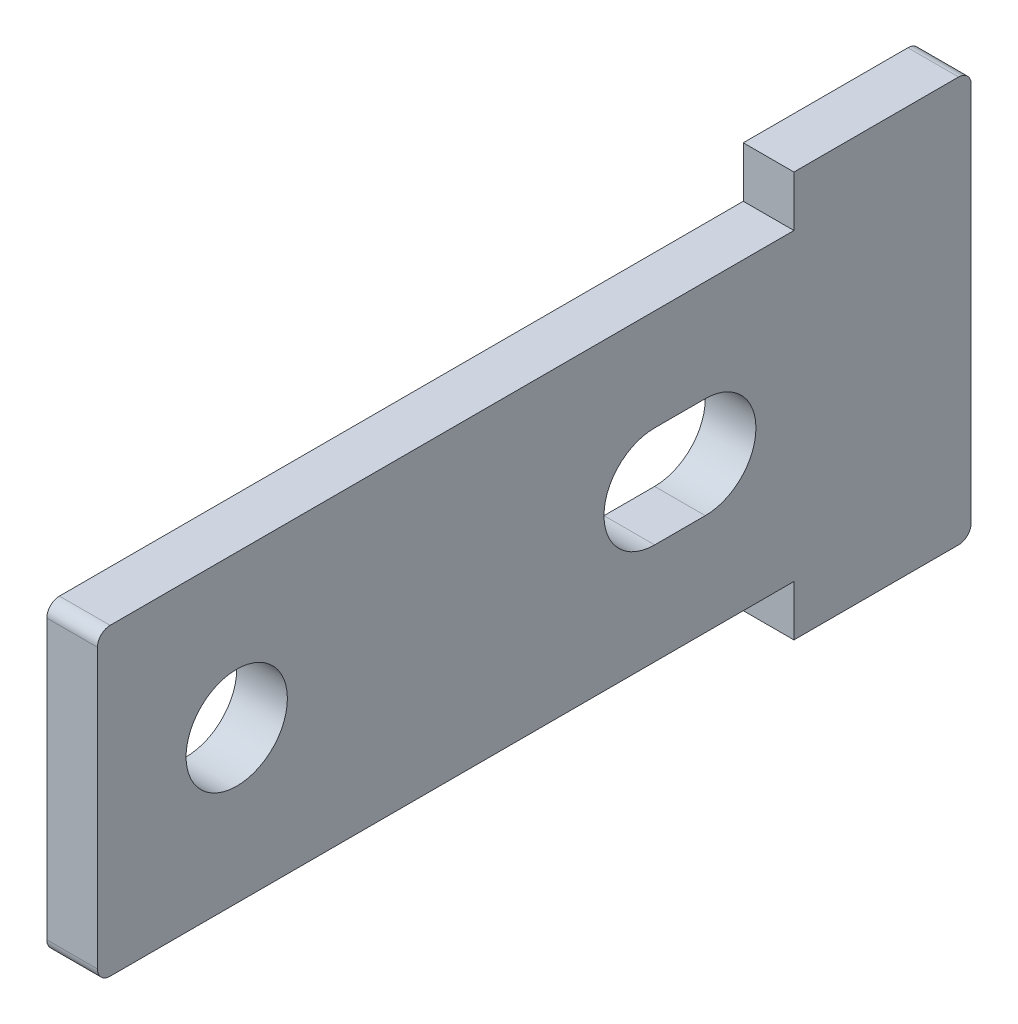
SolidWorks part; units mm, degrees
ref_plane "Front Plane" through (0, 0, 0) normal (1, 0, 0) x (0, 1, 0)
ref_plane "Top Plane" through (0, 0, 0) normal (0, 0, 1) x (0, 1, 0)
ref_plane "Right Plane" through (0, 0, 0) normal (0, 1, 0) x (-1, 0, 0)
sketch "Sketch1" plane through (0, 0, 0) normal (1, 0, 0) x (0, 1, 0)
  line L0 (0, 0) -> (8, 0)
  line L1 (8, 0) -> (8, 7)
  line L2 (8, 7) -> (6, 7)
  line L3 (6, 7) -> (6, 34.5)
  line L4 (6, 34.5) -> (-6, 34.5)
  line L5 (-6, 34.5) -> (-6, 7)
  line L6 (-6, 7) -> (-8, 7)
  line L7 (-8, 7) -> (-8, 0)
  line L8 (-8, 0) -> (0, 0)
  dimension "D1" = 34.5
  dimension "D2" = 12
  dimension "D3" = 16
  dimension "D4" = 7
extrude "Boss-Extrude1" add sketch "Sketch1" along normal blind 2 contours L5 L6 L7 L8 L0 L1 L2 L3 L4
fillet "Fillet1" radius 0.5 4 edges at (1, -8, 0) (1, 8, 0) (1, -6, 34.5) (1, 6, 34.5)
sketch "Sketch2" plane through (2, 0, 0) normal (1, 0, 0) x (0, 1, 0)
  line L0 (-2, 12.5) -> (-2, 10.5)
  line L1 (2, 12.5) -> (2, 10.5)
  line L2 (-7.5, 0) -> (7.5, 0) construction
  line L3 (5.5, 34.5) -> (-5.5, 34.5) construction
  circle A0 centre (0, 29) radius 2
  arc A1 (2, 12.5) -> (-2, 12.5) centre (0, 12.5) ccw
  arc A2 (2, 10.5) -> (-2, 10.5) centre (0, 10.5) cw
  point P11 (0, 0)
  point P12 (0, 0)
  point P13 (0, 13.6336)
  point P14 (0, 0)
  point P15 (0, 19.814)
  point P16 (0, 0)
  point P17 (0.9873, 17.1918)
  point P18 (0, 8.5)
  point P19 (0, 14.5)
  point P20 (0, 0)
  point P23 (0, 34.5)
  dimension "D5" = 4
  dimension "D1" = 29
  dimension "D2" = 4
  dimension "D3" = 6
  dimension "D4" = 26
extrude "Cut-Extrude1" cut sketch "Sketch2" against normal blind 2
